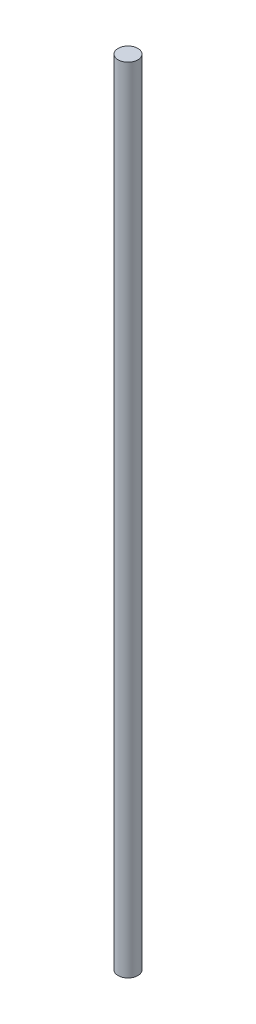
SolidWorks part; units mm, degrees
material "Stal stopowa (SS)"
ref_plane "Płaszczyzna przednia" through (0, 0, 0) normal (0, 0, 1) x (1, 0, 0)
ref_plane "Płaszczyzna górna" through (0, 0, 0) normal (0, 1, 0) x (1, 0, 0)
ref_plane "Płaszczyzna prawa" through (0, 0, 0) normal (1, 0, 0) x (0, 0, -1)
sketch "Szkic1" plane through (0, 0, 0) normal (0, 1, 0) x (1, 0, 0)
  circle A0 centre (0, 0) radius 5
  dimension "D1" = 10
extrude "Dodanie-wyciągnięcie1" add sketch "Szkic1" along normal blind 400
thread "Gwint1" pitch 1.25 start angle 0, offset 0, length 0, pitch 1.25, diameter 10
ref_plane "Płaszczyzna1" through (5, 0, 0) normal (0, 0, 1) x (1, 0, 0)
sketch "Profil gwintu1" plane through (5, 0, 0) normal (0, 0, 1) x (1, 0, 0)
  line L0 (0, 0) -> (0, 1.25) construction
  line L1 (0, 0) -> (0.6766, 0.3906)
  line L2 (0.6766, 0.3906) -> (0.6766, 0.5469)
  line L3 (0.6766, 0.5469) -> (0, 0.9375)
  line L4 (0.6766, 0.4687) -> (0, 0.4687) construction
  line L11 (0, 0) -> (0, 0.9375)
  point P2 (0, 0)
  dimension "Pitch" = 1.25
  dimension "Profile_Angle" = 60
  dimension "Profile_Land" = 0.1562
  dimension "Profile_Height" = 0.6766
